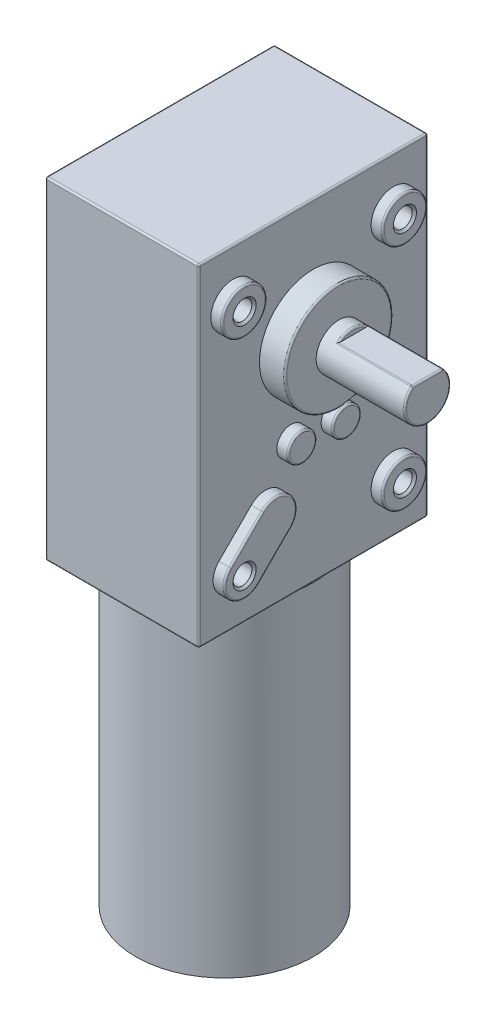
SolidWorks part; units mm, degrees
material "普通碳钢"
ref_plane "前视基准面" through (0, 0, 0) normal (0, 0, 1) x (1, 0, 0)
ref_plane "上视基准面" through (0, 0, 0) normal (0, 1, 0) x (1, 0, 0)
ref_plane "右视基准面" through (0, 0, 0) normal (1, 0, 0) x (0, 0, -1)
sketch "草图2" plane through (0, 0, 0) normal (0, 1, 0) x (1, 0, 0)
  line L1 (-13.4, 20) -> (13.4, 20)
  line L2 (-13.4, 20) -> (-13.4, -20)
  line L3 (-13.4, -20) -> (13.4, -20)
  line L4 (13.4, 20) -> (13.4, -20)
  line L5 (-13.4, 20) -> (13.4, -20) construction
  line L6 (-13.4, -20) -> (13.4, 20) construction
  point P0 (0, 0)
  dimension "D1" = 26.8
  dimension "D2" = 40
extrude "凸台-拉伸1" add sketch "草图2" along normal blind 58
sketch "草图3" plane through (13.4, 0, 0) normal (1, 0, 0) x (0, 0, -1)
  line L0 (-20, 58) -> (20, 0) construction
  line L1 (20, 58) -> (-20, 0) construction
  line L2 (-14, 9) -> (-8.3431, 14.6569) construction
  line L3 (-14, 49) -> (14, 49)
  line L4 (-14, 49) -> (-14, 9)
  line L5 (-14, 9) -> (14, 9)
  line L6 (14, 49) -> (14, 9)
  line L7 (-14, 49) -> (14, 9) construction
  line L8 (-14, 9) -> (14, 49) construction
  line L9 (-16.4749, 11.4749) -> (-10.818, 17.1317)
  line L10 (-11.5251, 6.5251) -> (-5.8683, 12.182)
  line L11 (-3.8773, 23.378) -> (3.8773, 23.378)
  circle A0 centre (-14, 49) radius 3.9
  circle A1 centre (14, 49) radius 3.9
  circle A2 centre (14, 9) radius 3.9
  arc A3 (-16.4749, 11.4749) -> (-11.5251, 6.5251) centre (-14, 9) ccw
  arc A4 (-5.8683, 12.182) -> (-10.818, 17.1317) centre (-8.3431, 14.6569) ccw
  circle A5 centre (-3.8773, 23.378) radius 2.5
  circle A6 centre (3.8773, 23.378) radius 2.5
  point P8 (0, 29)
  point P16 (-11.1716, 11.8284)
  dimension "D3" = 7.8
  dimension "D4" = 7.8
  dimension "D5" = 7.8
  dimension "D6" = 3.5
  dimension "D9" = 5
  dimension "D1" = 28
  dimension "D2" = 40
  dimension "D7" = 45
  dimension "D8" = 8
extrude "凸台-拉伸2" add sketch "草图3" along normal blind 2 contours L3 A0 L4 | L4 A0 L3 | L6 A1 L3 | L3 A1 L6 | L10 A4 L9 L4 L5 | L9 A3 L10 L5 L4 | L6 A2 L5 | L5 A2 L6 | A5 | A6
sketch "草图4" plane through (13.4, 0, 0) normal (1, 0, 0) x (0, 0, -1)
  line L0 (0, 58) -> (0, 0) construction
  line L1 (-20, 58) -> (20, 58) construction
  line L2 (-14, 49) -> (14, 49) construction
  circle A0 centre (0, 38) radius 9.4
  dimension "D2" = 18.8
  dimension "D1" = 11
extrude "凸台-拉伸3" add sketch "草图4" along normal blind 4.5
ref_plane "基准面1" through (0, 0, 0) normal (1, 0, 0) x (0, 0, -1)
mirror "镜向1" about plane through (0, 0, 0) normal (1, 0, 0) of "凸台-拉伸3", "凸台-拉伸2"
sketch "草图5" plane through (17.9, 0, 0) normal (1, 0, 0) x (0, 0, -1)
  circle A0 centre (0, 38) radius 4
  dimension "D1" = 8
extrude "凸台-拉伸4" add sketch "草图5" along normal blind 15.5
sketch "草图6" plane through (33.4, 0, 0) normal (1, 0, 0) x (0, 0, -1)
  line L0 (-2.6458, 41) -> (2.6458, 41)
  circle A0 centre (0, 38) radius 4 construction
  arc A2 (2.6458, 41) -> (-2.6458, 41) centre (0, 38) ccw
  dimension "D1" = 3
extrude "切除-拉伸1" cut sketch "草图6" against normal blind 13
fillet "圆角1" radius 0.3 37 edges at (33.4, 41, 0) (20.4, 42, 0) (26.9, 41, -2.6458) (26.9, 41, 2.6458) (33.4, 34, 0) (-17.9, 38, -9.4) (-15.4, 23.378, -6.3773) (-15.4, 23.378, 1.3773) (-15.4, 9, -17.9) (-15.4, 9.3536, 8.6967) (-15.4, 6.5251, 16.4749) (-15.4, 14.3033, 13.6464) (-15.4, 17.1317, 5.8683) (-15.4, 49, -17.9) (-15.4, 49, 10.1) (17.9, 38, -9.4) (15.4, 23.378, -6.3773) (15.4, 23.378, 1.3773) (15.4, 9, -17.9) (15.4, 6.5251, 16.4749) (15.4, 14.3033, 13.6464) (15.4, 17.1317, 5.8683) (15.4, 9.3536, 8.6967) (15.4, 49, -17.9) (15.4, 49, 10.1) (13.4, 0, 0) (0, 0, -20) (-13.4, 0, 0) (0, 0, 20) (13.4, 58, 0) (0, 58, -20) (-13.4, 58, 0) (0, 58, 20) (-13.4, 29, 20) (-13.4, 29, -20) (13.4, 29, -20) (13.4, 29, 20)
sketch "草图7" plane through (0, 0, 0) normal (0, -1, 0) x (1, 0, 0)
  line L0 (-13.4, 0) -> (13.4, 0) construction
  line L1 (-13.4, 9.4) -> (-13.4, -9.4) construction
  line L2 (13.4, -9.4) -> (13.4, 9.4) construction
  circle A0 centre (-2.1, 0) radius 15.5
  dimension "D1" = 31
extrude "凸台-拉伸5" add sketch "草图7" along normal blind 56.6
sketch "草图8" plane through (0, -56.6, 0) normal (0, -1, 0) x (1, 0, 0)
  line L0 (-17.6, 0) -> (13.4, 0) construction
  line L1 (-17.6, 9.4) -> (-17.6, -9.4) construction
  circle A0 centre (-2.1, 0) radius 15.5 construction
  circle A1 centre (-2.1, 0) radius 6
  dimension "D1" = 12
extrude "凸台-拉伸6" add sketch "草图8" along normal blind 2
sketch "草图9" plane through (0, -58.6, 0) normal (0, -1, 0) x (1, 0, 0)
  line L0 (-8.1, 0) -> (3.9, 0) construction
  circle A0 centre (-2.1, 0) radius 6 construction
  circle A1 centre (-2.1, 0) radius 6 construction
  circle A2 centre (-2.1, 0) radius 1
  dimension "D1" = 2
extrude "凸台-拉伸7" add sketch "草图9" along normal blind 1
hole_wizard "M4 螺纹孔5" positions "3D草图2" profile "草图14" tap size "M4" standard "GB"
sketch3d "3D草图2"
  line L0 (12.893, 49, -14) -> (19.514, 49, -14) construction
  line L1 (12.893, 49, 14) -> (19.514, 49, 14) construction
  line L2 (12.893, 9, -14) -> (19.514, 9, -14) construction
  line L3 (13.409, 9, 14) -> (18.482, 9, 14) construction
  point P0 (15.4, 49, -14)
  point P4 (15.4, 49, 14)
  point P8 (15.4, 9, -14)
  point P12 (15.4, 9, 14)
sketch "草图14" plane through (15.4, 49, -14) normal (0, 1, 0) x (0, 0, -1)
  line L0 (0, 0) -> (0, 11.0914)
  line L1 (0, 11.0914) -> (1.65, 10.1)
  line L2 (1.65, 10.1) -> (1.65, 0.375)
  line L3 (1.65, 0.375) -> (2.025, 0)
  line L5 (2.025, 0) -> (0, 0)
  line L6 (-1.65, 0.375) -> (-2.025, 0) construction
  line L10 (0, 11.0914) -> (-1.65, 10.1) construction
  line L11 (0, -6.35) -> (0, 107.95) construction
  dimension "螺纹孔钻头直径" = 3.3
  dimension "螺纹孔钻头深度" = 10.1
  dimension "近端锥形沉头孔直径" = 4.05
  dimension "近端锥形沉头孔角度" = 90
  dimension "导头角度" = 118
cosmetic thread "孔螺蚊线1" parameters "D1"=8, "D2"=4
cosmetic thread "孔螺蚊线2" parameters "D1"=8, "D2"=4
cosmetic thread "孔螺蚊线3" parameters "D1"=8, "D2"=4
cosmetic thread "孔螺蚊线4" parameters "D1"=8, "D2"=4
mirror "镜向2" about plane through (0, 0, 0) normal (1, 0, 0) of "M4 螺纹孔5"
cosmetic thread "孔螺蚊线5" parameters "D1"=8, "D2"=4
cosmetic thread "孔螺蚊线6" parameters "D1"=8, "D2"=4
cosmetic thread "孔螺蚊线7" parameters "D1"=8, "D2"=4
cosmetic thread "孔螺蚊线8" parameters "D1"=8, "D2"=4
